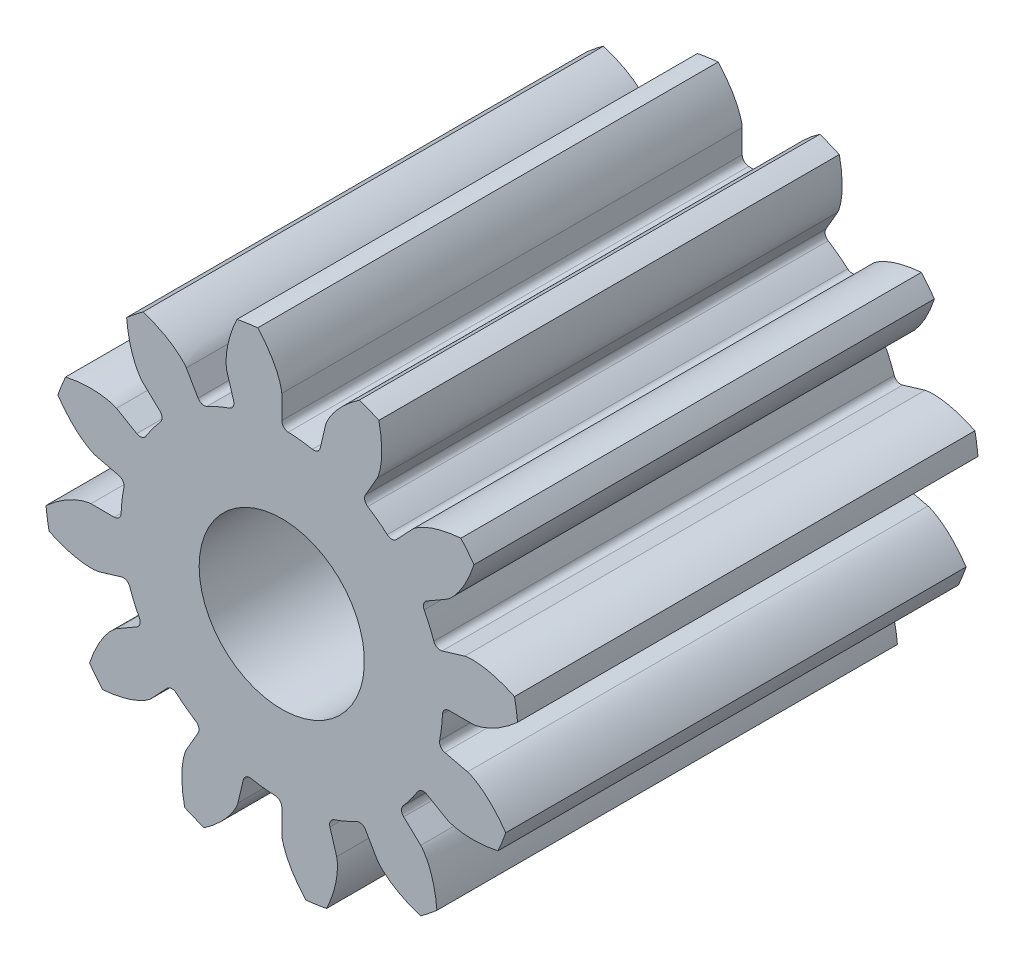
SolidWorks part; units mm, degrees
material "AISI 1020"
ref_plane "Front Plane" through (0, 0, 0) normal (0, 0, 1) x (1, 0, 0)
ref_plane "Top Plane" through (0, 0, 0) normal (0, 1, 0) x (1, 0, 0)
ref_plane "Right Plane" through (0, 0, 0) normal (1, 0, 0) x (0, 0, -1)
sketch "Sketch3" plane through (0, 0, 0) normal (0, 0, 1) x (1, 0, 0)
  circle A0 centre (0, 0) radius 3.5
  dimension "D1" = 7
extrude "Boss-Extrude1" add sketch "Sketch3" along normal blind 6.8 contours A0
sketch "Sketch4" plane through (0, 0, 0) normal (0, 0, 1) x (1, 0, 0)
  line L0 (2.375, 0) -> (2.8191, 0)
  line L1 (0, 0) -> (3.4765, -0.4051) construction
  line L2 (2.3114, -0.546) -> (2.7436, -0.6481)
  circle A0 centre (0, 0) radius 3 construction
  circle A1 centre (0, 0) radius 2.8191 construction
  arc A2 (2.3114, -0.546) -> (2.375, 0) centre (0, 0) ccw
  circle A3 centre (0, 0) radius 3.5 construction
  circle A4 centre (0, 0) radius 3.5 construction
  spline S0 degree 4 poles (2.8191, 0) (2.8212, 0) (2.827, 0.0003) (2.838, 0.0013) (2.8559, 0.0038) (2.889, 0.0099) (2.9282, 0.02) (2.9719, 0.034) (3.0182, 0.0516) (3.0572, 0.0682) (3.0957, 0.0862) (3.1335, 0.1055) (3.1786, 0.1303) (3.2319, 0.1621) (3.2927, 0.2023) (3.3598, 0.2513) (3.4261, 0.3048) (3.4896, 0.3603) (3.5516, 0.4196) (3.61, 0.4793) (3.6682, 0.5443) (3.7206, 0.6059) (3.7766, 0.6782) (3.8209, 0.7375) (3.8762, 0.819) (3.9079, 0.8681) (3.9438, 0.9267) (3.9592, 0.9533) (3.9687, 0.9696) knots 0 0 0 0 0 0.005377 0.015084 0.028532 0.04661 0.092111 0.119476 0.146842 0.174209 0.201575 0.228941 0.256307 0.307035 0.361767 0.4165 0.471232 0.525964 0.580697 0.635429 0.690161 0.744894 0.799626 0.854358 0.909091 0.954545 1 1 1 1 1 construction
  spline S1 degree 4 poles (2.8191, 0) (2.8212, 0) (2.827, 0.0003) (2.838, 0.0013) (2.8559, 0.0038) (2.889, 0.0099) (2.9282, 0.02) (2.9719, 0.034) (3.0182, 0.0516) (3.0572, 0.0682) (3.0957, 0.0862) (3.1335, 0.1055) (3.1786, 0.1303) (3.2319, 0.1621) (3.2927, 0.2023) (3.3598, 0.2513) (3.4261, 0.3048) (3.4896, 0.3603) (3.5516, 0.4196) (3.61, 0.4793) (3.6682, 0.5443) (3.7206, 0.6059) (3.7766, 0.6782) (3.8209, 0.7375) (3.8642, 0.8013) (3.8849, 0.8328) (3.8953, 0.849) knots 0 0 0 0 0 0.005377 0.015084 0.028532 0.04661 0.092111 0.119476 0.146842 0.174209 0.201575 0.228941 0.256307 0.307035 0.361767 0.4165 0.471232 0.525964 0.580697 0.635429 0.690161 0.744894 0.799626 0.854358 0.909091 0.909091 0.909091 0.909091 0.909091
  spline S2 degree 4 poles (2.7436, -0.6481) (2.7456, -0.6487) (2.7512, -0.6503) (2.7617, -0.6538) (2.7785, -0.6603) (2.8093, -0.6739) (2.8452, -0.6927) (2.8845, -0.7164) (2.9255, -0.7441) (2.9596, -0.7693) (2.9929, -0.7957) (3.0253, -0.8231) (3.0635, -0.8576) (3.108, -0.9008) (3.1579, -0.9539) (3.212, -1.017) (3.2643, -1.0844) (3.3133, -1.153) (3.36, -1.225) (3.4031, -1.2964) (3.4448, -1.3731) (3.4817, -1.4451) (3.5195, -1.5283) (3.549, -1.5962) (3.5764, -1.6683) (3.5894, -1.7037) (3.5958, -1.7219) knots 0 0 0 0 0 0.005377 0.015084 0.028532 0.04661 0.092111 0.119476 0.146842 0.174209 0.201575 0.228941 0.256307 0.307035 0.361767 0.4165 0.471232 0.525964 0.580697 0.635429 0.690161 0.744894 0.799626 0.854358 0.909091 0.909091 0.909091 0.909091 0.909091
  dimension "D1" = 6
  dimension "D2" = 5.6382
  dimension "D3" = 4.75
  dimension "D4" = 6.646
sketch "Sketch5" plane through (0, 0, 0) normal (0, 0, -1) x (-1, 0, 0)
sketch "Sketch7" plane through (0, 0, 0) normal (0, 0, -1) x (-1, 0, 0)
sketch "Sketch9" plane through (0, 0, 0) normal (0, 0, -1) x (-1, 0, 0)
  circle A0 centre (0, 0) radius 1.22
extrude "Cut-Extrude2" cut sketch "Sketch4" against normal through all and the other way through all
pattern_circular "CirPattern1" count 12 over 360 about axis through (0, 0, 6.8) along (0, 0, 1) of "Cut-Extrude2"
fillet "Fillet1" radius 0.1 24 edges at (2.0568, -1.1875, 3.4) (1.7287, -1.6286, 3.4) (1.1875, -2.0568, 3.4) (0.6828, -2.2747, 3.4) (0, -2.375, 3.4) (-0.546, -2.3114, 3.4) (-1.1875, -2.0568, 3.4) (-1.6286, -1.7287, 3.4) (-2.0568, -1.1875, 3.4) (-2.2747, -0.6828, 3.4) (-2.375, 0, 3.4) (-2.3114, 0.546, 3.4) (-2.0568, 1.1875, 3.4) (-1.7287, 1.6286, 3.4) (-1.1875, 2.0568, 3.4) (-0.6828, 2.2747, 3.4) (0.546, 2.3114, 3.4) (1.1875, 2.0568, 3.4) (1.6286, 1.7287, 3.4) (2.0568, 1.1875, 3.4) (2.2747, 0.6828, 3.4) (2.375, 0, 3.4) (2.3114, -0.546, 3.4) (0, 2.375, 3.4)
extrude "Cut-Extrude3" cut sketch "Sketch9" against normal through all
equation "\"P\"= 2'Diametral Pitch"
equation "\"N\"= 12'Numver of teeth"
equation "\"phi\"= 20deg'Pressure Angle"
equation "\"a\"= 1 / \"P\"'Addendum"
equation "\"b\"= 1.25 / \"P\"'Dedendun"
equation "\"c\"= \"b\" - \"a\"'clearance"
equation "\"dp\"= \"N\" / \"P\"'pitch circle diameter"
equation "\"db\"= \"dp\" * cos ( \"phi\" )'base circle diameter"
equation "\"D1@Sketch3\"= \"dp\" + 2 * \"a\""
equation "\"D1@Sketch4\"= \"dp\"'Pitch circle diametr"
equation "\"D2@Sketch4\"= \"db\"'Base Circle"
equation "\"alpha\"= sqr ( \"dp\" ^ 2 - \"db\" ^ 2 ) / \"db\" * 180 / pi - \"phi\""
equation "\"Beta\"= ( 360 / ( 4 * \"N\" ) - \"alpha\" ) * 2"
